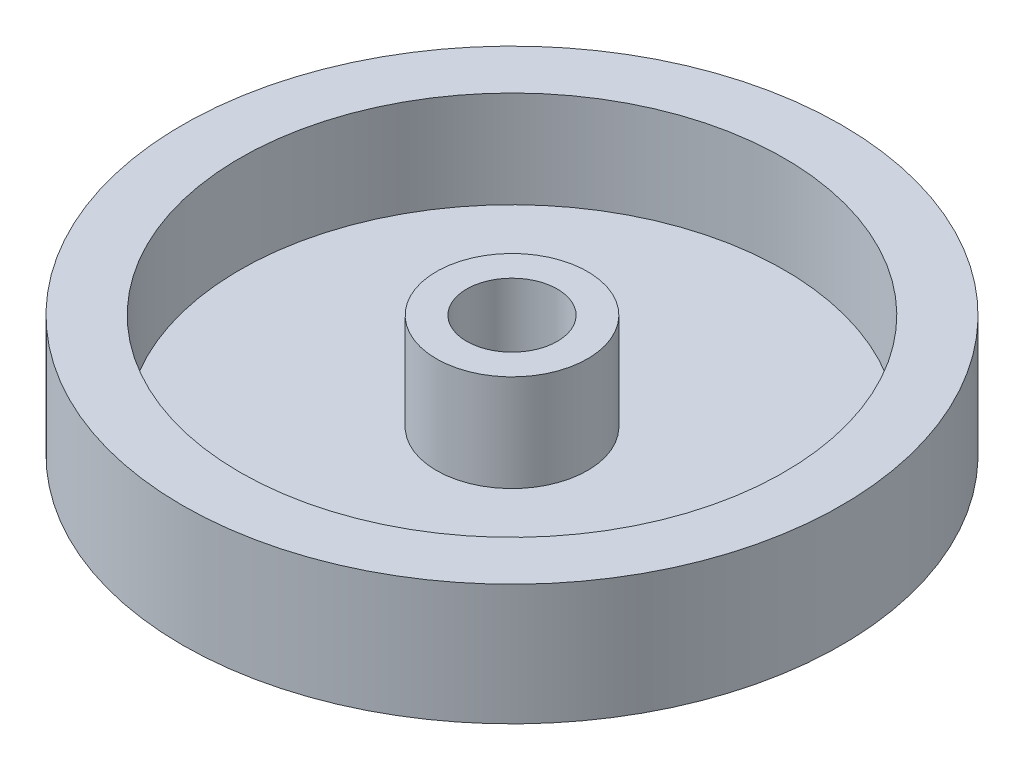
SolidWorks part; units mm, degrees
material "Автоматная латунь, UNS C36000"
ref_plane "Спереди" through (0, 0, 0) normal (0, 0, 1) x (1, 0, 0)
ref_plane "Сверху" through (0, 0, 0) normal (0, 1, 0) x (1, 0, 0)
ref_plane "Справа" through (0, 0, 0) normal (1, 0, 0) x (0, 0, -1)
sketch "Эскиз1" plane through (0, 0, 0) normal (0, 1, 0) x (1, 0, 0)
  circle A0 centre (0, 0) radius 10.9
extrude "Вытянуть1" add sketch "Эскиз1" along normal blind 4
sketch "Эскиз2" plane through (0, 4, 0) normal (0, 1, 0) x (1, 0, 0)
  circle A0 centre (0, 0) radius 9
  circle A1 centre (0, 0) radius 2.5
extrude "Вытянуть2" cut sketch "Эскиз2" against normal blind 3.2
sketch "Эскиз3" plane through (0, 4, 0) normal (0, 1, 0) x (1, 0, 0)
  circle A0 centre (0, 0) radius 1.5
extrude "Вытянуть3" cut sketch "Эскиз3" against normal through all
